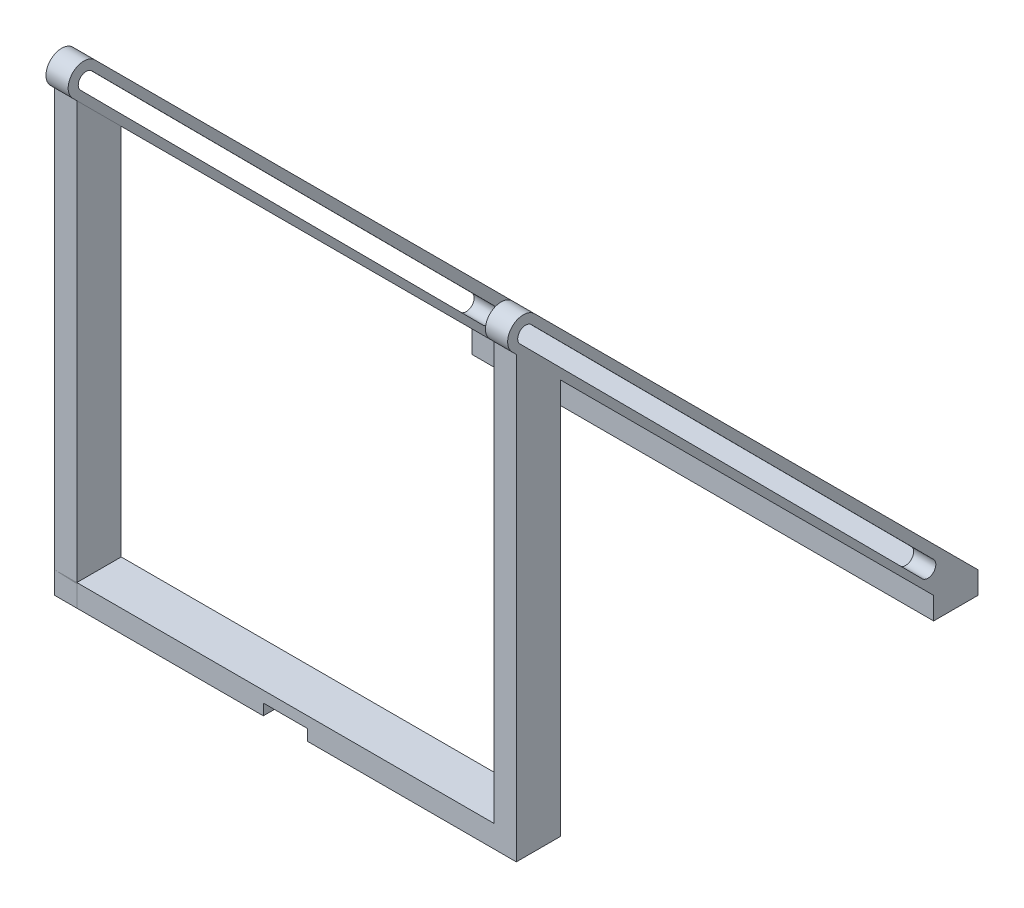
SolidWorks part; units mm, degrees
ref_plane "Front Plane" through (0, 0, 0) normal (0, 0, 1) x (1, 0, 0)
ref_plane "Top Plane" through (0, 0, 0) normal (0, 1, 0) x (1, 0, 0)
ref_plane "Right Plane" through (0, 0, 0) normal (1, 0, 0) x (0, 0, -1)
sketch "Sketch1" plane through (0, 0, 0) normal (0, 1, 0) x (1, 0, 0)
  line L0 (0, -462.534) -> (0, 462.534) construction
  line L1 (-462.534, -462.534) -> (462.534, -462.534)
  line L2 (-462.534, -462.534) -> (-462.534, 462.534)
  line L3 (-462.534, 462.534) -> (462.534, 462.534)
  line L4 (462.534, -462.534) -> (462.534, 462.534)
  line L5 (-462.534, -462.534) -> (462.534, 462.534) construction
  line L6 (-462.534, 462.534) -> (462.534, -462.534) construction
  line L8 (-44.45, -589.534) -> (44.45, -589.534)
  line L9 (-44.45, -589.534) -> (-44.45, -335.534)
  line L10 (-44.45, -335.534) -> (44.45, -335.534)
  line L11 (44.45, -589.534) -> (44.45, -335.534)
  line L12 (-44.45, -589.534) -> (44.45, -335.534) construction
  line L13 (-44.45, -335.534) -> (44.45, -589.534) construction
  point P0 (0, 0)
  dimension "D1" = 925.068
  dimension "D2" = 925.068
  dimension "D3" = 88.9
  dimension "D4" = 254
sketch "Sketch2" plane through (0, 0, 0) normal (0, 1, 0) x (1, 0, 0)
  line L0 (462.534, -462.534) -> (462.534, 462.534) construction
  line L1 (-462.534, 462.534) -> (462.534, 462.534)
  line L2 (-462.534, 462.534) -> (-462.534, 373.634)
  line L3 (-462.534, 373.634) -> (462.534, 373.634)
  line L4 (462.534, 462.534) -> (462.534, 373.634)
  line L6 (-462.534, -462.534) -> (462.534, -462.534)
  line L7 (-462.534, -462.534) -> (-462.534, -373.634)
  line L8 (-462.534, -373.634) -> (462.534, -373.634)
  line L9 (462.534, -462.534) -> (462.534, -373.634)
  dimension "D1" = 88.9
  dimension "D2" = 88.9
extrude "Boss-Extrude1" add sketch "Sketch2" along normal blind 44.45
sketch "Sketch3" plane through (-462.534, 0, 0) normal (-1, 0, 0) x (0, 0, 1)
  line L0 (-462.534, 44.45) -> (435.4916, 942.4756)
  line L1 (-462.534, 44.45) -> (-373.634, 44.45) construction
  dimension "D1" = 1270
  dimension "D2" = 45
sketch "Sketch4" plane through (0, 44.45, 0) normal (0, 1, 0) x (1, 0, 0)
  line L0 (-462.534, 373.634) -> (462.534, 373.634) construction
  line L1 (-462.534, 462.534) -> (-418.084, 462.534)
  line L2 (-462.534, 462.534) -> (-462.534, 373.634)
  line L3 (-462.534, 373.634) -> (-418.084, 373.634)
  line L4 (-418.084, 462.534) -> (-418.084, 373.634)
  dimension "D1" = 44.45
sweep "Sweep1" add profiles "Sketch4" path "Sketch3"
fillet "Fillet1" radius 31.4309 4 edges at (-462.534, 942.4756, 479.9416) (-440.309, 942.4756, 524.3916) (-418.084, 942.4756, 479.9416) (-440.309, 942.4756, 435.4916)
sketch "Sketch5" plane through (-462.534, 0, 0) normal (-1, 0, 0) x (0, 0, 1)
  line L0 (470.7357, 933.2697) -> (-457.4104, 0) construction
  line L1 (462.534, 0) -> (-462.534, 0) construction
  line L2 (-362.1261, 95.8103) -> (443.8692, 906.2549) construction
  line L3 (-373.3823, 107.0046) -> (432.613, 917.4493)
  line L4 (-350.87, 84.6159) -> (455.1254, 895.0605)
  arc A0 (470.7357, 888.8197) -> (426.2857, 933.2697) centre (448.5107, 911.0447) ccw construction
  arc A1 (-373.3823, 107.0046) -> (-350.87, 84.6159) centre (-362.1261, 95.8103) ccw
  arc A2 (455.1254, 895.0605) -> (432.613, 917.4493) centre (443.8692, 906.2549) ccw
  point P9 (40.8715, 501.0326)
  dimension "D4" = 38.1
  dimension "D1" = 1316.2247
  dimension "D2" = 31.75
  dimension "D3" = 1143
extrude "Cut-Extrude1" cut sketch "Sketch5" against normal blind 44.45
sketch "Sketch6" plane through (0, 44.45, 0) normal (0, 1, 0) x (1, 0, 0)
  line L0 (462.534, -373.634) -> (-462.534, -373.634) construction
  line L1 (-462.534, -462.534) -> (-418.084, -462.534)
  line L2 (-462.534, -462.534) -> (-462.534, -373.634)
  line L3 (-462.534, -373.634) -> (-418.084, -373.634)
  line L4 (-418.084, -462.534) -> (-418.084, -373.634)
  dimension "D1" = 44.45
extrude "Boss-Extrude2" add sketch "Sketch6" along normal up to surface and the other way blind 44.45 separate body up to face at (-440.309, 466.6349, 48.5509)
mirror "Mirror4" about plane through (0, 0, 0) normal (1, 0, 0) of "Boss-Extrude2"
mirror "Mirror8" about plane through (0, 0, 0) normal (1, 0, 0) of "Fillet1", "Cut-Extrude1", "Sweep1"
extrude "Cut-Extrude2" cut sketch "Sketch1" along normal blind 22.225 contours L9 L10 L11 L8
